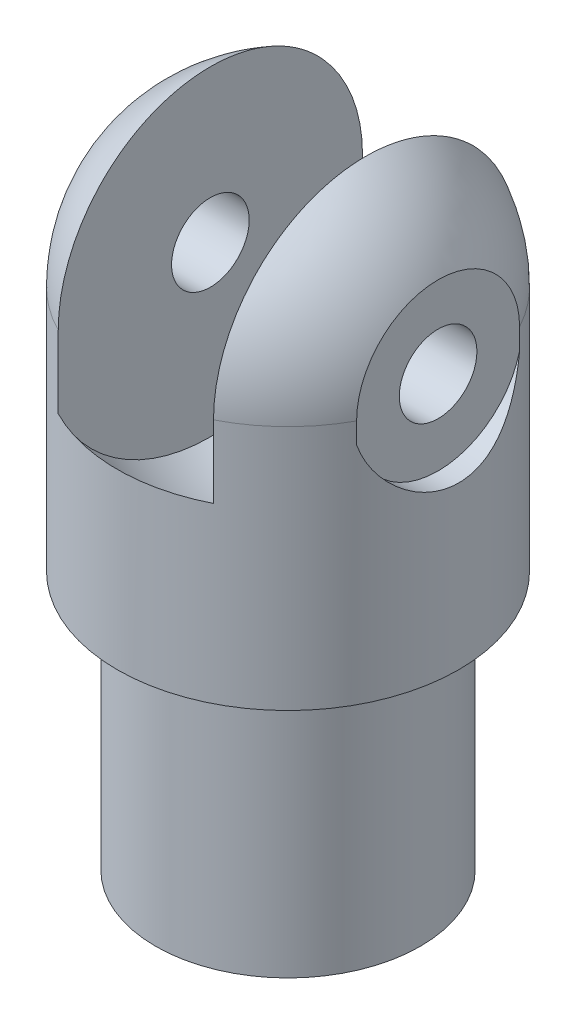
SolidWorks part; units mm, degrees
ref_plane "Front Plane" through (0, 0, 0) normal (0, 0, 1) x (1, 0, 0)
ref_plane "Top Plane" through (0, 0, 0) normal (0, 1, 0) x (1, 0, 0)
ref_plane "Right Plane" through (0, 0, 0) normal (1, 0, 0) x (0, 0, -1)
sketch "Sketch1" plane through (0, 0, 0) normal (0, 1, 0) x (1, 0, 0)
  circle A0 centre (0, 0) radius 12.9921
extrude "Boss-Extrude1" add sketch "Sketch1" along normal blind 25.4 contours A0
sketch "Sketch2" plane through (0, 0, 0) normal (1, 0, 0) x (0, 0, -1)
  line L0 (-16.764, 25.4) -> (-16.764, 49.53)
  line L1 (0, 25.4) -> (-16.764, 25.4)
  line L4 (12.9921, 25.4) -> (-12.9921, 25.4) construction
  line L5 (0, 14.2913) -> (0, -14.2913) construction
  line L6 (0, 25.4) -> (0, 66.294)
  arc A0 (0, 66.294) -> (-16.764, 49.53) centre (0, 49.53) ccw
  dimension "D1" = 33.528
  dimension "D2" = 24.13
revolve "Revolve1" add sketch "Sketch2" angle 360 about L6
sketch "Sketch3" plane through (0, 0, 0) normal (1, 0, 0) x (0, 0, -1)
  line L2 (16.764, 49.53) -> (-16.764, 49.53) construction
  circle A2 centre (0, 49.53) radius 3.81
extrude "Cut-Extrude1" cut sketch "Sketch3" against normal through all both and the other way through all
sketch "Sketch4" plane through (0, 0, 0) normal (0, 0, 1) x (1, 0, 0)
  line L0 (16.3253, 49.53) -> (-16.3253, 49.53) construction
  line L1 (-7.62, 32.9954) -> (-7.62, 49.53)
  line L2 (-7.62, 49.53) -> (7.62, 49.53)
  line L3 (7.62, 49.53) -> (7.62, 32.9954)
  arc A0 (-7.62, 32.9954) -> (7.62, 32.9954) centre (0, 49.53) ccw
  dimension "D1" = 15.24
revolve "Cut-Revolve1" cut sketch "Sketch4" angle 360 about L2
ref_plane "Plane1" through (16.764, 0, 0) normal (1, 0, 0) x (0, 0, -1)
sketch "Sketch6" plane through (16.764, 0, 0) normal (1, 0, 0) x (0, 0, -1)
  circle A0 centre (0, 49.53) radius 8.255
extrude "Cut-Extrude2" cut sketch "Sketch6" against normal blind 2.032
mirror "Mirror1" about plane through (0, 0, 0) normal (1, 0, 0) of "Cut-Extrude2"
